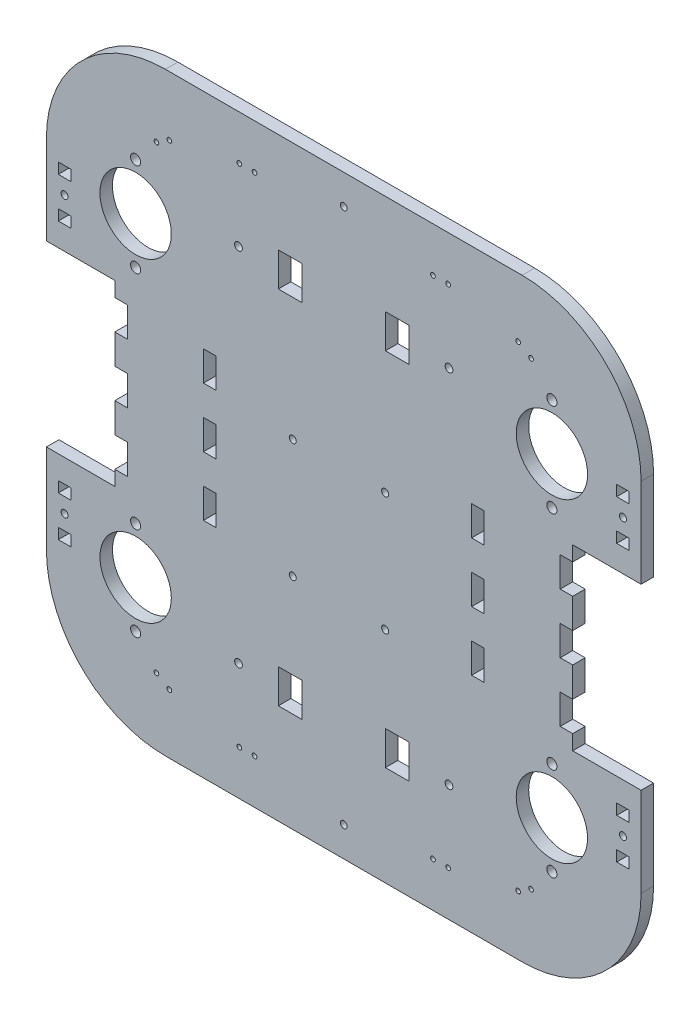
SolidWorks part; units mm, degrees
material "Oak"
ref_plane "Front Plane" through (0, 0, 0) normal (0, 0, 1) x (1, 0, 0)
ref_plane "Top Plane" through (0, 0, 0) normal (0, 1, 0) x (1, 0, 0)
ref_plane "Right Plane" through (0, 0, 0) normal (1, 0, 0) x (0, 0, -1)
sketch "Sketch1" plane through (0, 0, 0) normal (0, 0, 1) x (1, 0, 0)
  line L1 (50.8, 0) -> (203.2, 0)
  line L2 (0, 50.8) -> (0, 203.2)
  line L3 (50.8, 254) -> (203.2, 254)
  line L4 (254, 50.8) -> (254, 203.2)
  arc A0 (0, 203.2) -> (50.8, 254) centre (50.8, 203.2) cw
  arc A1 (254, 203.2) -> (203.2, 254) centre (203.2, 203.2) ccw
  arc A2 (0, 50.8) -> (50.8, 0) centre (50.8, 50.8) ccw
  arc A3 (254, 50.8) -> (203.2, 0) centre (203.2, 50.8) cw
  point P9 (254, 254)
  point P12 (0, 0)
  point P15 (254, 0)
  dimension "D3" = 50.8
  dimension "D4" = 50.8
  dimension "D5" = 50.8
  dimension "D6" = 50.8
  dimension "D1" = 254
  dimension "D2" = 254
extrude "Boss-Extrude1" add sketch "Sketch1" along normal blind 5.334
sketch "Sketch3" plane through (0, 0, 5.334) normal (0, 0, 1) x (1, 0, 0)
  line L0 (29.21, 95.25) -> (29.21, 88.9)
  line L5 (203.2, 254) -> (50.8, 254) construction
  line L6 (29.21, 120.65) -> (29.21, 107.95)
  line L11 (0, 203.2) -> (0, 50.8) construction
  line L12 (29.21, 133.35) -> (34.544, 133.35)
  line L14 (29.21, 120.65) -> (34.544, 120.65)
  line L15 (34.544, 133.35) -> (34.544, 120.65)
  line L16 (29.21, 158.75) -> (34.544, 158.75)
  line L18 (29.21, 146.05) -> (34.544, 146.05)
  line L19 (34.544, 158.75) -> (34.544, 146.05)
  line L20 (29.21, 107.95) -> (34.544, 107.95)
  line L22 (29.21, 95.25) -> (34.544, 95.25)
  line L23 (34.544, 107.95) -> (34.544, 95.25)
  line L24 (224.79, 133.35) -> (219.456, 133.35)
  line L26 (224.79, 120.65) -> (219.456, 120.65)
  line L27 (219.456, 133.35) -> (219.456, 120.65)
  line L28 (224.79, 158.75) -> (219.456, 158.75)
  line L30 (224.79, 146.05) -> (219.456, 146.05)
  line L31 (219.456, 158.75) -> (219.456, 146.05)
  line L32 (224.79, 107.95) -> (219.456, 107.95)
  line L34 (224.79, 95.25) -> (219.456, 95.25)
  line L35 (219.456, 107.95) -> (219.456, 95.25)
  line L36 (67.056, 133.35) -> (72.39, 133.35)
  line L37 (67.056, 133.35) -> (67.056, 120.65)
  line L38 (67.056, 120.65) -> (72.39, 120.65)
  line L39 (72.39, 133.35) -> (72.39, 120.65)
  line L40 (67.056, 158.75) -> (72.39, 158.75)
  line L41 (67.056, 158.75) -> (67.056, 146.05)
  line L42 (67.056, 146.05) -> (72.39, 146.05)
  line L43 (72.39, 158.75) -> (72.39, 146.05)
  line L44 (67.056, 107.95) -> (72.39, 107.95)
  line L45 (67.056, 107.95) -> (67.056, 95.25)
  line L46 (67.056, 95.25) -> (72.39, 95.25)
  line L47 (72.39, 107.95) -> (72.39, 95.25)
  line L48 (186.944, 158.75) -> (181.61, 158.75)
  line L49 (186.944, 158.75) -> (186.944, 146.05)
  line L50 (186.944, 146.05) -> (181.61, 146.05)
  line L51 (181.61, 158.75) -> (181.61, 146.05)
  line L52 (186.944, 133.35) -> (181.61, 133.35)
  line L53 (186.944, 133.35) -> (186.944, 120.65)
  line L54 (186.944, 120.65) -> (181.61, 120.65)
  line L55 (181.61, 133.35) -> (181.61, 120.65)
  line L56 (186.944, 107.95) -> (181.61, 107.95)
  line L57 (186.944, 107.95) -> (186.944, 95.25)
  line L58 (186.944, 95.25) -> (181.61, 95.25)
  line L59 (181.61, 107.95) -> (181.61, 95.25)
  line L60 (0, 165.1) -> (29.21, 165.1)
  line L61 (0, 165.1) -> (0, 88.9)
  line L62 (0, 88.9) -> (29.21, 88.9)
  line L63 (29.21, 165.1) -> (29.21, 158.75)
  line L64 (254, 50.8) -> (254, 203.2) construction
  line L65 (254, 165.1) -> (224.79, 165.1)
  line L66 (254, 165.1) -> (254, 88.9)
  line L67 (254, 88.9) -> (224.79, 88.9)
  line L68 (224.79, 165.1) -> (224.79, 158.75)
  line L69 (29.21, 146.05) -> (29.21, 133.35)
  line L70 (224.79, 146.05) -> (224.79, 133.35)
  line L71 (224.79, 120.65) -> (224.79, 107.95)
  line L72 (224.79, 95.25) -> (224.79, 88.9)
  point P38 (222.123, 107.95)
  dimension "D7" = 5.334
  dimension "D8" = 12.7
  dimension "D9" = 120.65
  dimension "D10" = 5.334
  dimension "D11" = 5.334
  dimension "D12" = 12.7
  dimension "D13" = 12.7
  dimension "D14" = 12.7
  dimension "D15" = 12.7
  dimension "D16" = 5.334
  dimension "D17" = 5.334
  dimension "D18" = 5.334
  dimension "D19" = 12.7
  dimension "D20" = 12.7
  dimension "D21" = 12.7
  dimension "D22" = 12.7
  dimension "D23" = 12.7
  dimension "D24" = 120.65
  dimension "D25" = 5.334
  dimension "D26" = 5.334
  dimension "D27" = 5.334
  dimension "D28" = 12.7
  dimension "D29" = 12.7
  dimension "D30" = 12.7
  dimension "D31" = 12.7
  dimension "D32" = 12.7
  dimension "D33" = 0
  dimension "D34" = 0
  dimension "D35" = 0
  dimension "D37" = 5.334
  dimension "D38" = 5.334
  dimension "D39" = 5.334
  dimension "D40" = 12.7
  dimension "D41" = 12.7
  dimension "D42" = 12.7
  dimension "D43" = 12.7
  dimension "D44" = 12.7
  dimension "D45" = 0
  dimension "D46" = 0
  dimension "D47" = 0
  dimension "D5" = 76.2
  dimension "D6" = 29.21
  dimension "D36" = 88.9
  dimension "D50" = 29.21
  dimension "D51" = 76.2
  dimension "D52" = 88.9
  dimension "D57" = 43.18
extrude "Cut-Extrude1" cut sketch "Sketch3" against normal blind 5.334
sketch "Sketch4" plane through (0, 0, 5.334) normal (0, 0, 1) x (1, 0, 0)
  line L0 (102.2134, 118.999) -> (147.6794, 118.999) construction
  line L1 (102.2134, 90.678) -> (147.6794, 90.678)
  line L2 (102.2134, 90.678) -> (102.2134, 147.32)
  line L3 (102.2134, 147.32) -> (147.6794, 147.32)
  line L4 (147.6794, 90.678) -> (147.6794, 147.32)
  line L5 (124.9464, 147.32) -> (124.9464, 90.678) construction
  line L6 (203.2, 254) -> (50.8, 254) construction
  circle A0 centre (105.2134, 93.678) radius 1.5
  circle A1 centre (144.6794, 93.678) radius 1.5
  circle A2 centre (144.6794, 144.32) radius 1.5
  circle A3 centre (105.2134, 144.32) radius 1.5
  point P0 (124.9464, 129.0347)
  dimension "D3" = 3
  dimension "D1" = 45.466
  dimension "D2" = 56.642
  dimension "D4" = 3
  dimension "D5" = 3
  dimension "D6" = 106.68
extrude "Cut-Extrude2" cut sketch "Sketch4" against normal through all contours A3 | A2 | A1 | A0
sketch "Sketch5" plane through (0, 0, 5.334) normal (0, 0, 1) x (1, 0, 0)
  line L0 (254, 165.1) -> (224.79, 165.1) construction
  line L1 (74.93, 211.328) -> (109.22, 211.328)
  line L2 (74.93, 211.328) -> (74.93, 196.85)
  line L3 (74.93, 196.85) -> (109.22, 196.85)
  line L4 (109.22, 211.328) -> (109.22, 196.85)
  line L5 (144.78, 211.328) -> (179.07, 211.328)
  line L6 (144.78, 211.328) -> (144.78, 196.85)
  line L7 (144.78, 196.85) -> (179.07, 196.85)
  line L8 (179.07, 211.328) -> (179.07, 196.85)
  line L9 (29.21, 165.1) -> (0, 165.1) construction
  line L10 (127, 254) -> (127, 0) construction
  line L11 (203.2, 254) -> (50.8, 254) construction
  line L12 (50.8, 0) -> (203.2, 0) construction
  line L15 (99.06, 211.328) -> (99.06, 196.85)
  line L16 (154.94, 211.328) -> (154.94, 196.85)
  line L17 (34.544, 127) -> (219.456, 127) construction
  line L18 (34.544, 120.65) -> (34.544, 133.35) construction
  line L19 (219.456, 133.35) -> (219.456, 120.65) construction
  line L20 (154.94, 42.672) -> (154.94, 57.15)
  line L21 (99.06, 42.672) -> (99.06, 57.15)
  line L22 (179.07, 42.672) -> (179.07, 57.15)
  line L23 (144.78, 57.15) -> (179.07, 57.15)
  line L24 (144.78, 42.672) -> (144.78, 57.15)
  line L25 (144.78, 42.672) -> (179.07, 42.672)
  line L26 (109.22, 42.672) -> (109.22, 57.15)
  line L27 (74.93, 57.15) -> (109.22, 57.15)
  line L28 (74.93, 42.672) -> (74.93, 57.15)
  line L29 (74.93, 42.672) -> (109.22, 42.672)
  circle A0 centre (82.042, 204.089) radius 1.651
  circle A1 centre (171.958, 204.089) radius 1.651
  circle A2 centre (171.958, 49.911) radius 1.651
  circle A3 centre (82.042, 49.911) radius 1.651
  dimension "D11" = 3.302
  dimension "D12" = 3.302
  dimension "D13" = 7.112
  dimension "D1" = 14.478
  dimension "D2" = 14.478
  dimension "D3" = 31.75
  dimension "D4" = 31.75
  dimension "D5" = 34.29
  dimension "D6" = 34.29
  dimension "D7" = 35.56
  dimension "D8" = 17.78
  dimension "D9" = 10.16
  dimension "D10" = 10.16
  dimension "D14" = 7.112
  dimension "D15" = 7.239
  dimension "D16" = 7.239
extrude "Cut-Extrude3" cut sketch "Sketch5" against normal through all contours A0 | L1 L15 L3 L4 | L16 L5 L6 L7 | A1 | A3 | L21 L29 L26 L27 | L24 L25 L20 L23 | A2
sketch "Sketch6" plane through (0, 0, 5.334) normal (0, 0, 1) x (1, 0, 0)
  line L0 (34.544, 127) -> (219.456, 127) construction
  line L1 (34.544, 120.65) -> (34.544, 133.35) construction
  line L2 (219.456, 133.35) -> (219.456, 120.65) construction
  line L3 (127, 254) -> (127, 0) construction
  line L4 (203.2, 254) -> (50.8, 254) construction
  line L5 (50.8, 0) -> (203.2, 0) construction
  line L6 (0, 203.2) -> (0, 165.1) construction
  line L7 (5.08, 196.85) -> (10.414, 196.85)
  line L8 (5.08, 196.85) -> (5.08, 192.278)
  line L9 (5.08, 192.278) -> (10.414, 192.278)
  line L10 (10.414, 196.85) -> (10.414, 192.278)
  line L11 (5.08, 196.85) -> (10.414, 192.278) construction
  line L12 (5.08, 192.278) -> (10.414, 196.85) construction
  line L13 (5.08, 175.006) -> (10.414, 175.006)
  line L14 (5.08, 175.006) -> (5.08, 179.578)
  line L15 (5.08, 179.578) -> (10.414, 179.578)
  line L16 (10.414, 175.006) -> (10.414, 179.578)
  line L17 (5.08, 175.006) -> (10.414, 179.578) construction
  line L18 (5.08, 179.578) -> (10.414, 175.006) construction
  line L19 (248.92, 179.578) -> (243.586, 175.006) construction
  line L20 (248.92, 175.006) -> (243.586, 179.578) construction
  line L21 (248.92, 192.278) -> (243.586, 196.85) construction
  line L22 (248.92, 196.85) -> (243.586, 192.278) construction
  line L23 (243.586, 175.006) -> (243.586, 179.578)
  line L24 (248.92, 179.578) -> (243.586, 179.578)
  line L25 (248.92, 175.006) -> (248.92, 179.578)
  line L26 (248.92, 175.006) -> (243.586, 175.006)
  line L27 (243.586, 196.85) -> (243.586, 192.278)
  line L28 (248.92, 192.278) -> (243.586, 192.278)
  line L29 (248.92, 196.85) -> (248.92, 192.278)
  line L30 (248.92, 196.85) -> (243.586, 196.85)
  line L31 (248.92, 57.15) -> (243.586, 61.722) construction
  line L32 (248.92, 61.722) -> (243.586, 57.15) construction
  line L33 (248.92, 78.994) -> (243.586, 74.422) construction
  line L34 (248.92, 74.422) -> (243.586, 78.994) construction
  line L35 (5.08, 74.422) -> (10.414, 78.994) construction
  line L36 (5.08, 78.994) -> (10.414, 74.422) construction
  line L37 (5.08, 61.722) -> (10.414, 57.15) construction
  line L38 (5.08, 57.15) -> (10.414, 61.722) construction
  line L39 (248.92, 57.15) -> (243.586, 57.15)
  line L40 (248.92, 57.15) -> (248.92, 61.722)
  line L41 (248.92, 61.722) -> (243.586, 61.722)
  line L42 (243.586, 57.15) -> (243.586, 61.722)
  line L43 (248.92, 78.994) -> (243.586, 78.994)
  line L44 (248.92, 78.994) -> (248.92, 74.422)
  line L45 (248.92, 74.422) -> (243.586, 74.422)
  line L46 (243.586, 78.994) -> (243.586, 74.422)
  line L47 (10.414, 78.994) -> (10.414, 74.422)
  line L48 (5.08, 74.422) -> (10.414, 74.422)
  line L49 (5.08, 78.994) -> (5.08, 74.422)
  line L50 (5.08, 78.994) -> (10.414, 78.994)
  line L51 (10.414, 57.15) -> (10.414, 61.722)
  line L52 (5.08, 61.722) -> (10.414, 61.722)
  line L53 (5.08, 57.15) -> (5.08, 61.722)
  line L54 (5.08, 57.15) -> (10.414, 57.15)
  circle A0 centre (7.747, 185.928) radius 1.5
  circle A1 centre (246.253, 185.928) radius 1.5
  circle A2 centre (246.253, 68.072) radius 1.5
  circle A3 centre (7.747, 68.072) radius 1.5
  point P12 (7.747, 194.564)
  point P17 (7.747, 177.292)
  point P37 (246.253, 177.292)
  point P38 (246.253, 194.564)
  point P59 (246.253, 59.436)
  point P60 (246.253, 76.708)
  point P61 (7.747, 76.708)
  point P62 (7.747, 59.436)
  dimension "D10" = 3
  dimension "D1" = 5.334
  dimension "D2" = 4.572
  dimension "D3" = 6.35
  dimension "D4" = 4.572
  dimension "D5" = 12.7
  dimension "D6" = 5.334
  dimension "D7" = 5.08
  dimension "D8" = 5.08
  dimension "D9" = 6.35
  dimension "D11" = 2.667
extrude "Cut-Extrude4" cut sketch "Sketch6" against normal through all
sketch "Sketch7" plane through (0, 0, 5.334) normal (0, 0, 1) x (1, 0, 0)
  line L0 (34.544, 127) -> (219.456, 127) construction
  line L1 (34.544, 120.65) -> (34.544, 133.35) construction
  line L2 (219.456, 133.35) -> (219.456, 120.65) construction
  line L3 (127, 0) -> (127, 254) construction
  line L4 (50.8, 0) -> (203.2, 0) construction
  line L5 (203.2, 254) -> (50.8, 254) construction
  circle A0 centre (82.4, 19.05) radius 1
  circle A1 centre (88.9, 19.05) radius 1
  circle A2 centre (165.1, 19.05) radius 1
  circle A3 centre (171.6, 19.05) radius 1
  circle A4 centre (171.6, 234.95) radius 1
  circle A5 centre (165.1, 234.95) radius 1
  circle A6 centre (88.9, 234.95) radius 1
  circle A7 centre (82.4, 234.95) radius 1
  circle A8 centre (127, 12.7) radius 1.45
  circle A9 centre (127, 241.3) radius 1.45
  circle A10 centre (52.5183, 25.4) radius 1
  circle A11 centre (46.99, 28.8188) radius 1
  circle A12 centre (207.01, 28.8188) radius 1
  circle A13 centre (201.4817, 25.4) radius 1
  circle A14 centre (201.4817, 228.6) radius 1
  circle A15 centre (207.01, 225.1812) radius 1
  circle A16 centre (46.99, 225.1812) radius 1
  circle A17 centre (52.5183, 228.6) radius 1
  dimension "D1" = 2
  dimension "D2" = 2
  dimension "D8" = 2.9
  dimension "D9" = 2
  dimension "D10" = 2
  dimension "D3" = 6.5
  dimension "D4" = 38.1
  dimension "D5" = 19.05
  dimension "D6" = 19.05
  dimension "D7" = 12.7
  dimension "D11" = 6.5
  dimension "D12" = 25.4
  dimension "D13" = 46.99
extrude "Cut-Extrude5" cut sketch "Sketch7" against normal through all
sketch "Sketch8" plane through (0, 0, 5.334) normal (0, 0, 1) x (1, 0, 0)
  line L0 (0, 88.9) -> (0, 50.8) construction
  line L5 (50.8, 0) -> (203.2, 0) construction
  line L6 (34.544, 127) -> (219.456, 127) construction
  line L7 (34.544, 120.65) -> (34.544, 133.35) construction
  line L8 (219.456, 133.35) -> (219.456, 120.65) construction
  line L9 (127, 254) -> (127, 0) construction
  line L10 (203.2, 254) -> (50.8, 254) construction
  circle A0 centre (38.1, 59.69) radius 15.24
  circle A1 centre (38.1, 39.751) radius 2.159
  circle A2 centre (38.1, 79.629) radius 2.159
  circle A3 centre (215.9, 79.629) radius 2.159
  circle A4 centre (215.9, 39.751) radius 2.159
  circle A5 centre (215.9, 59.69) radius 15.24
  circle A6 centre (215.9, 194.31) radius 15.24
  circle A7 centre (215.9, 214.249) radius 2.159
  circle A8 centre (215.9, 174.371) radius 2.159
  circle A9 centre (38.1, 174.371) radius 2.159
  circle A10 centre (38.1, 214.249) radius 2.159
  circle A11 centre (38.1, 194.31) radius 15.24
  dimension "D1" = 30.48
  dimension "D3" = 4.318
  dimension "D4" = 4.318
  dimension "D2" = 39.878
  dimension "D5" = 19.939
  dimension "D6" = 38.1
  dimension "D7" = 59.69
extrude "Cut-Extrude6" cut sketch "Sketch8" against normal through all
equation "\"Base_Width\"= 10in"
equation "\"Base_Length\"= 10in"
equation "\"Wheel_Width\"= 3in"
equation "\"MDF\"= 0.21in"
equation "\"D1@Sketch1\"=\"Base_Width\""
equation "\"D2@Sketch1\"=\"Base_Length\""
equation "\"D1@Boss-Extrude1\"=\"MDF\""
equation "\"D1@Cut-Extrude1\"=\"MDF\""
equation "\"D7@Sketch3\"=\"MDF\""
equation "\"D9@Sketch3\"=\"Base_Length\"/2 - 0.25in"
equation "\"D10@Sketch3\"=\"MDF\""
equation "\"D11@Sketch3\"=\"MDF\""
equation "\"D16@Sketch3\"=\"MDF\""
equation "\"D17@Sketch3\"=\"MDF\""
equation "\"D18@Sketch3\"=\"MDF\""
equation "\"D19@Sketch3\"=0.5"
equation "\"D20@Sketch3\"=0.5"
equation "\"D21@Sketch3\"=0.5in"
equation "\"D24@Sketch3\"=\"Base_Length\"/2 -0.25in"
equation "\"D25@Sketch3\"=\"MDF\""
equation "\"D26@Sketch3\"=\"MDF\""
equation "\"D27@Sketch3\"=\"MDF\""
equation "\"D37@Sketch3\"=\"MDF\""
equation "\"D38@Sketch3\"=\"MDF\""
equation "\"D39@Sketch3\"=\"MDF\""
equation "\"D5@Sketch3\"=\"Wheel_Width\""
equation "\"D36@Sketch3\"=\"Base_Length\"/2 -\"Wheel_Width\"/2"
equation "\"D51@Sketch3\"=\"Wheel_Width\""
equation "\"D52@Sketch3\"=\"Base_Length\"/2 -\"Wheel_Width\"/2"
